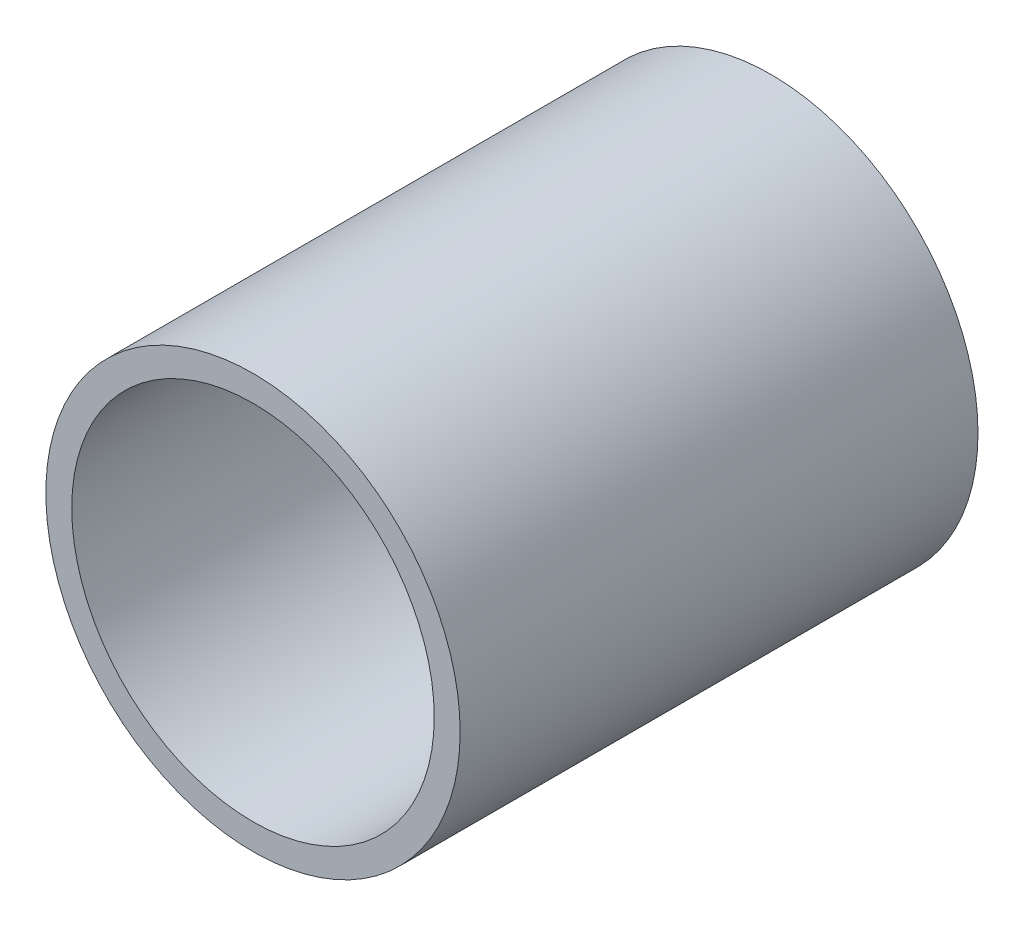
SolidWorks part; units mm, degrees
ref_plane "Alzado" through (0, 0, 0) normal (0, 0, 1) x (1, 0, 0)
ref_plane "Planta" through (0, 0, 0) normal (0, 1, 0) x (1, 0, 0)
ref_plane "Vista lateral" through (0, 0, 0) normal (1, 0, 0) x (0, 0, -1)
sketch "Croquis1" plane through (0, 0, 0) normal (0, 0, 1) x (1, 0, 0)
  circle A0 centre (0, 0) radius 4
  circle A1 centre (0, 0) radius 3.5
  dimension "D1" = 8
  dimension "D2" = 7
extrude "Saliente-Extruir1" add sketch "Croquis1" along normal blind 10
